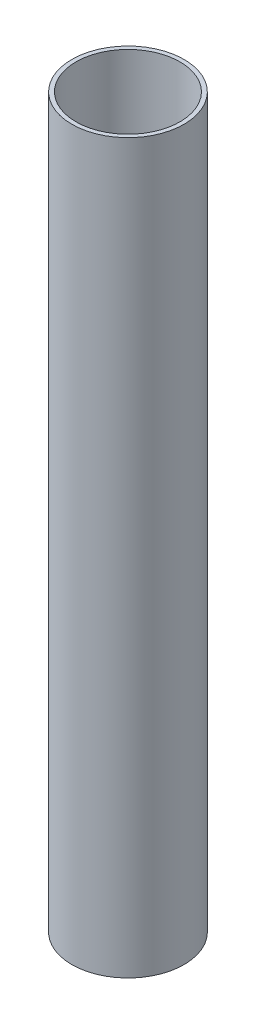
SolidWorks part; units mm, degrees
material "Thornel Mat VMA"
ref_plane "Front Plane" through (0, 0, 0) normal (0, 0, 1) x (1, 0, 0)
ref_plane "Top Plane" through (0, 0, 0) normal (0, 1, 0) x (1, 0, 0)
ref_plane "Right Plane" through (0, 0, 0) normal (1, 0, 0) x (0, 0, -1)
sketch "Sketch2" plane through (0, 0, 0) normal (0, 1, 0) x (1, 0, 0)
  circle A0 centre (0, 0) radius 13.716
  circle A1 centre (0, 0) radius 12.7
  dimension "D1" = 25.4
  dimension "D2" = 1.016
extrude "Boss-Extrude1" add sketch "Sketch2" along normal blind 177.8
